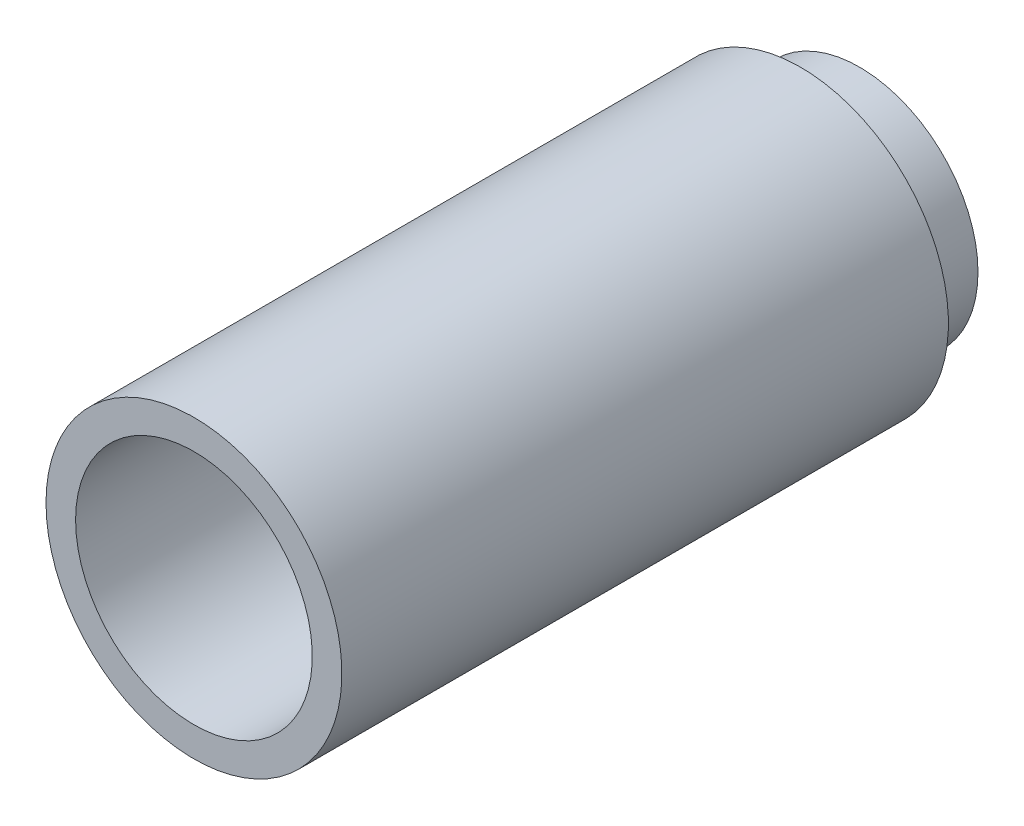
SolidWorks part; units mm, degrees
ref_plane "Front" through (0, 0, 0) normal (0, 0, 1) x (1, 0, 0)
ref_plane "Top" through (0, 0, 0) normal (0, 1, 0) x (1, 0, 0)
ref_plane "Right" through (0, 0, 0) normal (1, 0, 0) x (0, 0, -1)
sketch "草图1" plane through (0, 0, 0) normal (0, 0, 1) x (1, 0, 0)
  circle A0 centre (0, 0) radius 40
  circle A1 centre (0, 0) radius 35
extrude "凸台-拉伸1" add sketch "草图1" along normal blind 20
sketch "草图2" plane through (0, 0, 20) normal (0, 0, 1) x (1, 0, 0)
  circle A0 centre (0, 0) radius 50
  circle A1 centre (0, 0) radius 40
extrude "凸台-拉伸3" add sketch "草图2" along normal blind 205 separate body
